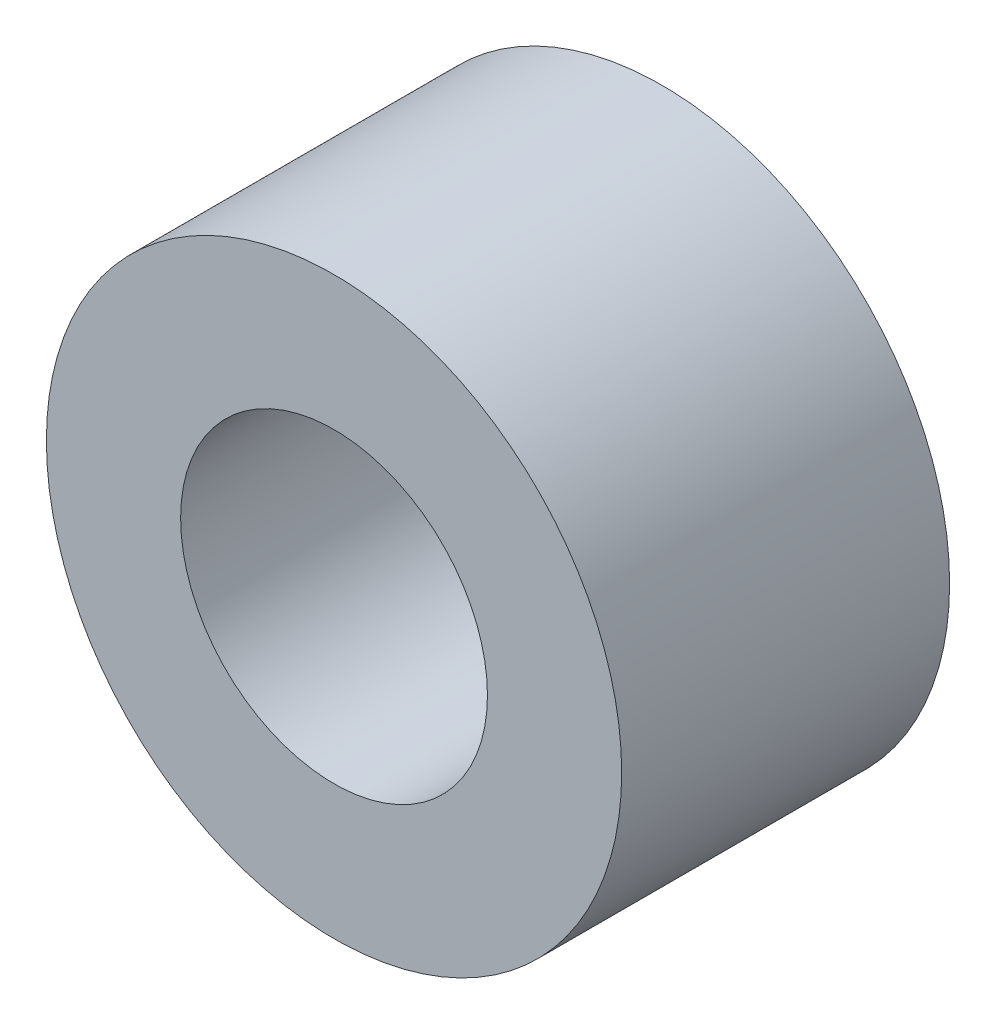
SolidWorks part; units mm, degrees
ref_plane "Plan de face" through (0, 0, 0) normal (0, 0, 1) x (1, 0, 0)
ref_plane "Plan de dessus" through (0, 0, 0) normal (0, 1, 0) x (1, 0, 0)
ref_plane "Plan de droite" through (0, 0, 0) normal (1, 0, 0) x (0, 0, -1)
sketch "Esquisse1" plane through (0, 0, 0) normal (0, 0, 1) x (1, 0, 0)
  circle A0 centre (0, 0) radius 3.2
  circle A1 centre (0, 0) radius 6
  dimension "D1" = 6.4
  dimension "D2" = 12
extrude "Boss.-Extru.1" add sketch "Esquisse1" along normal mid plane 6.84
